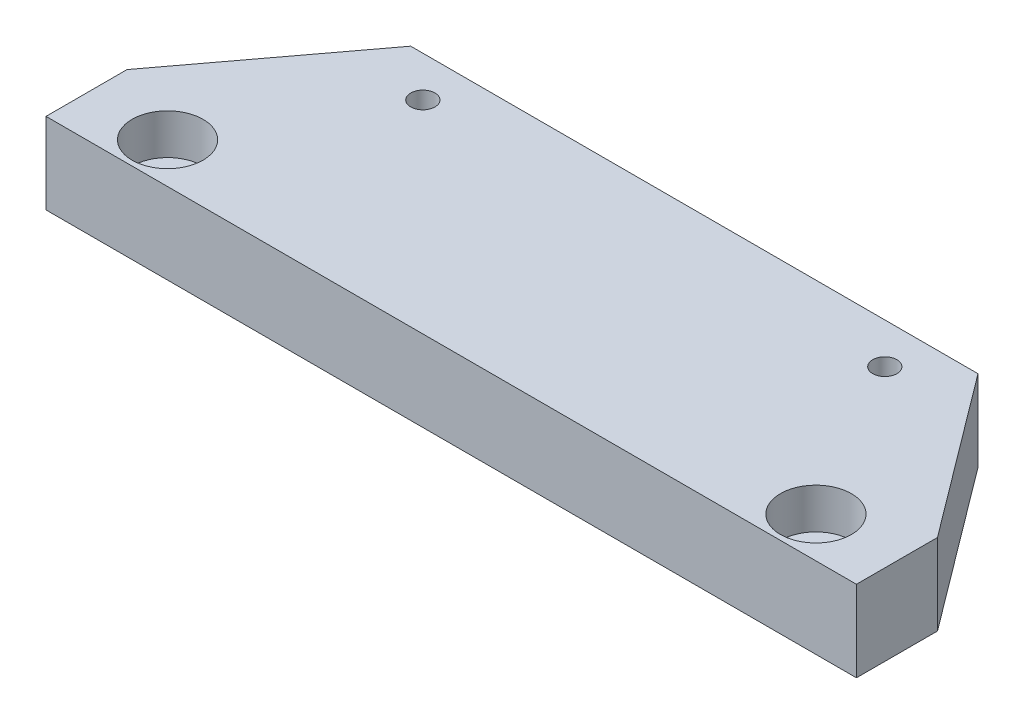
SolidWorks part; units mm, degrees
ref_plane "Front Plane" through (0, 0, 0) normal (0, 0, 1) x (1, 0, 0)
ref_plane "Top Plane" through (0, 0, 0) normal (0, 1, 0) x (1, 0, 0)
ref_plane "Right Plane" through (0, 0, 0) normal (1, 0, 0) x (0, 0, -1)
sketch "Sketch8" plane through (0, 0, 0) normal (0, 1, 0) x (1, 0, 0)
  line L0 (44.45, 0) -> (44.45, -12.7)
  line L1 (0, 0) -> (88.9, 0)
  line L2 (0, 0) -> (0, -12.7)
  line L3 (0, -12.7) -> (88.9, -12.7)
  line L4 (88.9, 0) -> (88.9, -12.7)
  line L5 (8.255, -6.35) -> (80.645, -6.35)
  line L6 (44.45, -12.7) -> (44.45, -31.75)
  line L7 (0, 0) -> (-19.05, -25.4)
  line L8 (-19.05, -25.4) -> (107.95, -25.4)
  line L9 (-19.05, -25.4) -> (-19.05, -38.1)
  line L10 (-19.05, -38.1) -> (107.95, -38.1)
  line L11 (107.95, -25.4) -> (107.95, -38.1)
  line L12 (-19.05, -25.4) -> (107.95, -38.1) construction
  line L13 (-19.05, -38.1) -> (107.95, -25.4) construction
  line L14 (88.9, 0) -> (107.95, -25.4)
  line L15 (95.25, -31.75) -> (-6.35, -31.75)
  point P10 (44.45, -6.35)
  point P23 (44.45, -31.75)
  dimension "D1" = 12.7
  dimension "D2" = 88.9
  dimension "D3" = 72.39
  dimension "D4" = 12.7
  dimension "D5" = 127
  dimension "D6" = 12.7
  dimension "D7" = 101.6
extrude "Boss-Extrude3" add sketch "Sketch8" along normal blind 12.7 contours L7 L8 L6 L3 L2 | L14 L4 L3 L6 L8
hole_wizard "CBORE for #6 Socket Head Cap Screw1" positions "Sketch11" profile "Sketch12" counterbore size "#6" standard "ANSI Inch" end condition up to next
sketch "Sketch11" plane through (0, 0, 0) normal (0, -1, 0) x (-1, 0, 0)
  point P0 (-80.645, -6.35)
  point P3 (-8.255, -6.35)
sketch "Sketch12" plane through (80.645, 0, 6.35) normal (1, 0, 0) x (0, 0, -1)
  line L0 (0, 0) -> (0, 12.7)
  line L1 (0, 12.7) -> (1.8986, 12.7)
  line L3 (1.8986, 12.7) -> (1.8986, 3.5052)
  line L4 (1.8986, 3.5052) -> (3.5725, 3.5052)
  line L5 (3.5725, 3.5052) -> (3.5725, 0)
  line L7 (3.5725, 0) -> (0, 0)
  line L11 (0, -6.35) -> (0, 107.95) construction
  dimension "Thru Hole Dia." = 3.7973
  dimension "Thru Hole Depth" = 12.7
  dimension "C'Bore Dia." = 7.145
  dimension "C'Bore Depth" = 3.5052
hole_wizard "CBORE for 1/4 Socket Head Cap Screw1" positions "Sketch13" profile "Sketch14" counterbore size "1/4" standard "ANSI Inch" end condition up to next
sketch "Sketch13" plane through (0, 12.7, 0) normal (0, 1, 0) x (1, 0, 0)
  point P0 (-6.35, -31.75)
  point P3 (95.25, -31.75)
sketch "Sketch14" plane through (-6.35, 12.7, 31.75) normal (1, 0, 0) x (0, 0, 1)
  line L0 (0, 0) -> (0, 12.7)
  line L1 (0, 12.7) -> (3.3782, 12.7)
  line L3 (3.3782, 12.7) -> (3.3782, 6.35)
  line L4 (3.3782, 6.35) -> (5.5562, 6.35)
  line L5 (5.5562, 6.35) -> (5.5562, 0)
  line L7 (5.5562, 0) -> (0, 0)
  line L11 (0, -6.35) -> (0, 107.95) construction
  dimension "Thru Hole Dia." = 6.7564
  dimension "Thru Hole Depth" = 12.7
  dimension "C'Bore Dia." = 11.1125
  dimension "C'Bore Depth" = 6.35
